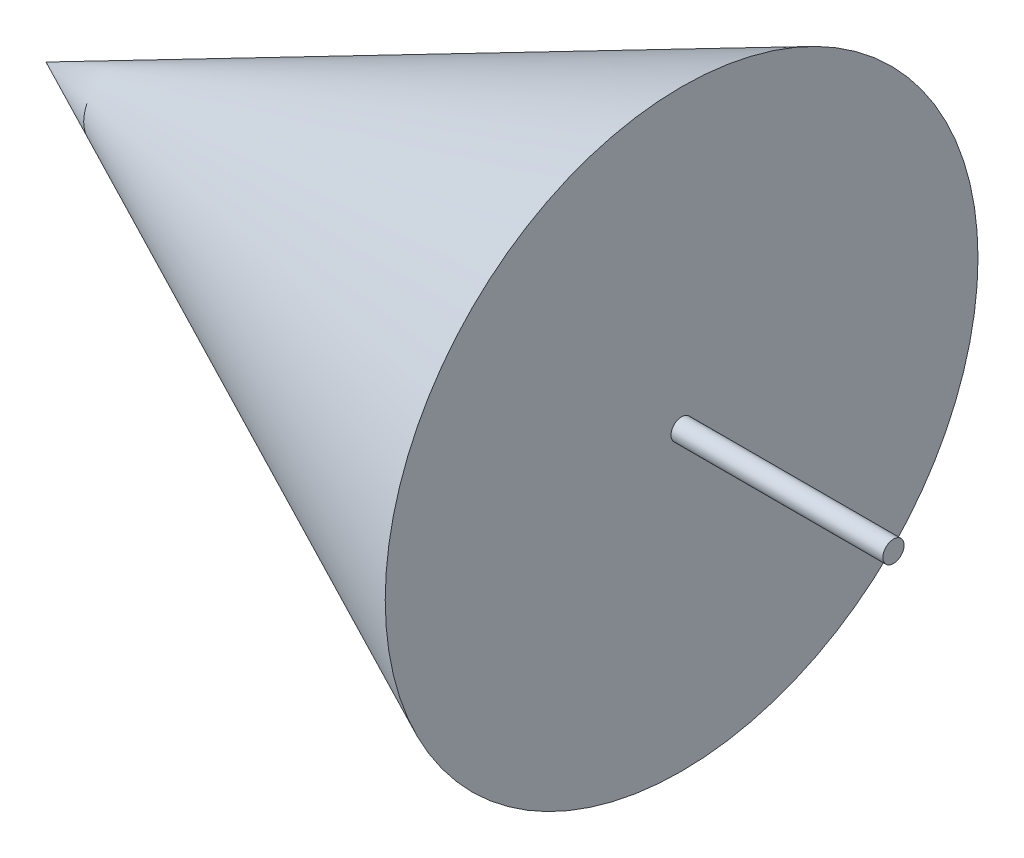
SolidWorks part; units mm, degrees
ref_plane "Plan de face" through (0, 0, 0) normal (0, 0, 1) x (1, 0, 0)
ref_plane "Plan de dessus" through (0, 0, 0) normal (0, 1, 0) x (1, 0, 0)
ref_plane "Plan de droite" through (0, 0, 0) normal (1, 0, 0) x (0, 0, -1)
sketch "Esquisse1" plane through (0, 0, 0) normal (0, 0, 1) x (1, 0, 0)
  line L0 (0, 0) -> (12, 0) construction
  line L1 (0, 0) -> (6, 2.7978)
  line L2 (6, 2.7978) -> (6, 0.1)
  line L3 (0, 0) -> (8, 0)
  line L4 (6, 0.1) -> (8, 0.1)
  line L5 (8, 0.1) -> (8, 0)
  dimension "D1" = 6
  dimension "D2" = 25
  dimension "D3" = 0.2
  dimension "D4" = 2
revolve "Révolution1" add sketch "Esquisse1" angle 360 about L0
